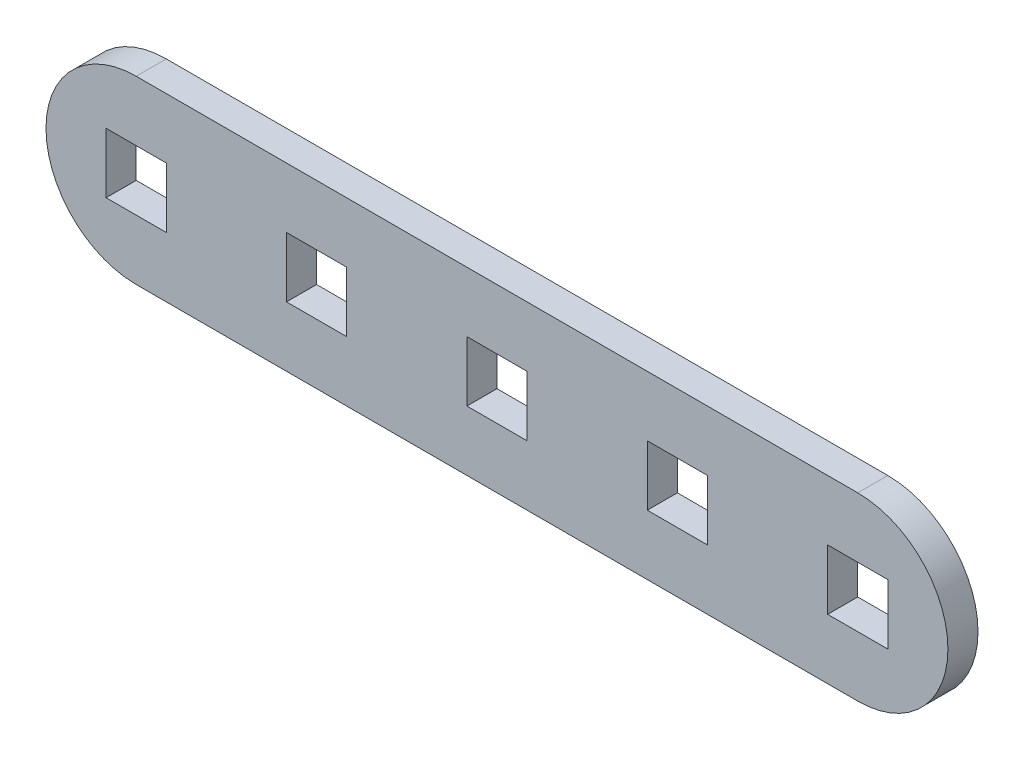
SolidWorks part; units mm, degrees
ref_plane "Alzado" through (0, 0, 0) normal (0, 0, 1) x (1, 0, 0)
ref_plane "Planta" through (0, 0, 0) normal (0, 1, 0) x (1, 0, 0)
ref_plane "Vista lateral" through (0, 0, 0) normal (1, 0, 0) x (0, 0, -1)
sketch "Model" plane through (0, 0, 0) normal (0, 0, 1) x (1, 0, 0)
  line L0 (9.9127, 294.2399) -> (9.9127, 291.2399)
  line L1 (12.9127, 294.2399) -> (9.9127, 294.2399)
  line L2 (12.9127, 291.2399) -> (12.9127, 294.2399)
  line L3 (9.9127, 291.2399) -> (12.9127, 291.2399)
  line L4 (18.9127, 294.2399) -> (18.9127, 291.2399)
  line L5 (21.9127, 294.2399) -> (18.9127, 294.2399)
  line L6 (21.9127, 291.2399) -> (21.9127, 294.2399)
  line L7 (18.9127, 291.2399) -> (21.9127, 291.2399)
  line L8 (27.9127, 294.2399) -> (27.9127, 291.2399)
  line L9 (30.9127, 294.2399) -> (27.9127, 294.2399)
  line L10 (30.9127, 291.2399) -> (30.9127, 294.2399)
  line L11 (27.9127, 291.2399) -> (30.9127, 291.2399)
  line L12 (36.9127, 294.2399) -> (36.9127, 291.2399)
  line L13 (39.9127, 294.2399) -> (36.9127, 294.2399)
  line L14 (39.9127, 291.2399) -> (39.9127, 294.2399)
  line L15 (36.9127, 291.2399) -> (39.9127, 291.2399)
  line L16 (45.9127, 294.2399) -> (45.9127, 291.2399)
  line L17 (48.9127, 294.2399) -> (45.9127, 294.2399)
  line L18 (48.9127, 291.2399) -> (48.9127, 294.2399)
  line L19 (45.9127, 291.2399) -> (48.9127, 291.2399)
  line L20 (11.4127, 297.2399) -> (47.4127, 297.2399)
  line L21 (11.4127, 288.2399) -> (47.4127, 288.2399)
  arc A0 (47.4127, 288.2399) -> (47.4127, 297.2399) centre (47.4127, 292.7399) ccw
  arc A1 (11.4127, 297.2399) -> (11.4127, 288.2399) centre (11.4127, 292.7399) ccw
extrude "Saliente-Extruir1" add sketch "Model" along normal blind 1.5
